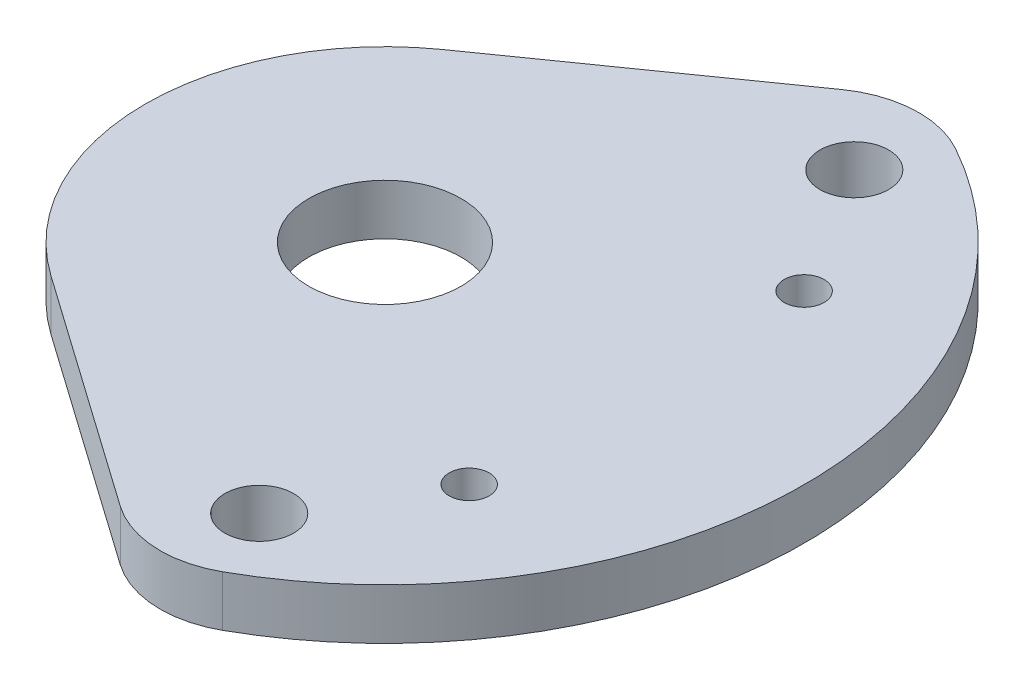
SolidWorks part; units mm, degrees
material "6061 Alloy"
ref_plane "Front Plane" through (0, 0, 0) normal (0, 0, 1) x (1, 0, 0)
ref_plane "Top Plane" through (0, 0, 0) normal (0, 1, 0) x (1, 0, 0)
ref_plane "Right Plane" through (0, 0, 0) normal (1, 0, 0) x (0, 0, -1)
sketch "Sketch1" plane through (0, 0, 0) normal (0, 1, 0) x (1, 0, 0)
  line L0 (0, 0) -> (8.978, -24.6669) construction
  line L6 (0, 0) -> (8.978, 24.6669) construction
  line L7 (0, 0) -> (-26.25, 0) construction
  line L8 (8.978, -24.6669) -> (-8.6358, -12.2647)
  line L9 (8.978, 24.6669) -> (-8.6358, 12.2647)
  circle A2 centre (0, 0) radius 4.7625
  circle A3 centre (0, 0) radius 26.25
  circle A4 centre (0, 0) radius 15
  dimension "D3" = 110
  dimension "D5" = 52.5
  dimension "D6" = 9.525
  dimension "D1" = 30
  dimension "D2" = 110
extrude "Boss-Extrude1" add sketch "Sketch1" along normal mid plane 3.175
hole_wizard "M4 Clearance Hole1" positions "Sketch6" profile "Sketch7" hole size "M4" standard "ANSI Metric" end condition up to next
sketch "Sketch6" plane through (0, 1.5875, 0) normal (0, 1, 0) x (1, 0, 0)
  line L0 (0, 0) -> (10.75, 18.6195)
  line L1 (0, 0) -> (10.75, -18.6195)
  line L2 (0, 0) -> (-21.5, 0)
  point P2 (10.75, 18.6195)
  point P10 (10.75, -18.6195)
  dimension "D1" = 21.5
  dimension "D2" = 120
  dimension "D3" = 120
sketch "Sketch7" plane through (10.75, 1.5875, 18.6195) normal (1, 0, 0) x (0, 0, 1)
  line L0 (0, 0) -> (0, 3.175)
  line L1 (0, 3.175) -> (2.15, 3.175)
  line L2 (2.15, 3.175) -> (2.15, 0)
  line L5 (2.15, 0) -> (0, 0)
  line L11 (0, -6.35) -> (0, 107.95) construction
  dimension "Thru Hole Dia." = 4.3
  dimension "Thru Hole Depth" = 3.175
hole_wizard "M3x0.5 Tapped Hole1" positions "Sketch8" profile "Sketch9" tap size "M3x0.5" standard "ANSI Metric" end condition up to next
sketch "Sketch8" plane through (0, 1.5875, 0) normal (0, 1, 0) x (1, 0, 0)
  line L2 (-1000, 0) -> (49000, 0) construction
  line L3 (0, 0) -> (15.75, 0) construction
  line L5 (15.75, -10.48) -> (15.75, 10.48) construction
  point P20 (0, 0)
  point P47 (15.75, -10.48)
  point P50 (15.75, 10.48)
  dimension "D1" = 15.75
  dimension "D2" = 90
  dimension "D3" = 20.96
sketch "Sketch9" plane through (0, 1.5875, 0) normal (1, 0, 0) x (0, 0, 1)
  line L0 (0, 0) -> (0, 3.175)
  line L1 (0, 3.175) -> (1.25, 3.175)
  line L2 (1.25, 3.175) -> (1.25, 0)
  line L5 (1.25, 0) -> (0, 0)
  line L11 (0, -6.35) -> (0, 107.95) construction
  dimension "Thru Tap Drill Dia." = 2.5
  dimension "Thru Tap Drill Depth" = 3.175
cosmetic thread "Hole Thread1" parameters "D2"=3
cosmetic thread "Hole Thread6" parameters "D2"=3
fillet "Fillet1" radius 6.35 2 edges at (8.978, 0, -24.6669) (8.978, 0, 24.6669)
